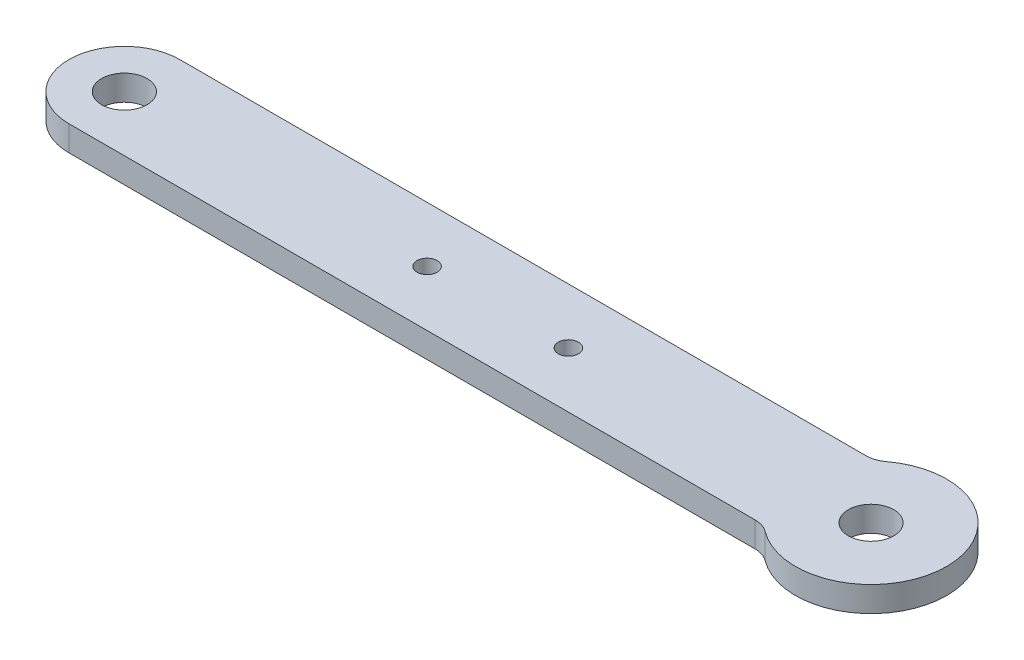
SolidWorks part; units mm, degrees
ref_plane "前视基准面" through (0, 0, 0) normal (0, 0, 1) x (1, 0, 0)
ref_plane "上视基准面" through (0, 0, 0) normal (0, 1, 0) x (1, 0, 0)
ref_plane "右视基准面" through (0, 0, 0) normal (1, 0, 0) x (0, 0, -1)
sketch "草图1" plane through (0, 0, 0) normal (0, 1, 0) x (1, 0, 0)
  line L0 (-64.2327, 19.038) -> (71.7673, 19.038)
  line L5 (71.7673, -2.962) -> (-64.2327, -2.962)
  arc A0 (-64.2327, 19.038) -> (-64.2327, -2.962) centre (-64.2327, 8.038) ccw
  circle A1 centre (-64.2327, 8.038) radius 4.5
  arc A2 (74.7673, -3.962) -> (74.7673, 20.038) centre (83.7673, 8.038) ccw
  circle A3 centre (83.7673, 8.038) radius 4.5
  circle A4 centre (-4.2327, 8.038) radius 2
  circle A5 centre (23.7673, 8.038) radius 2
  arc A6 (71.7673, 19.038) -> (74.7673, 20.038) centre (71.7673, 24.038) ccw
  arc A7 (71.7673, -2.962) -> (74.7673, -3.962) centre (71.7673, -7.962) cw
  dimension "D4" = 60
  dimension "D1" = 5
  dimension "D2" = 5
  dimension "D3" = 11
  dimension "D5" = 28
extrude "凸台-拉伸1" add sketch "草图1" along normal blind 5
